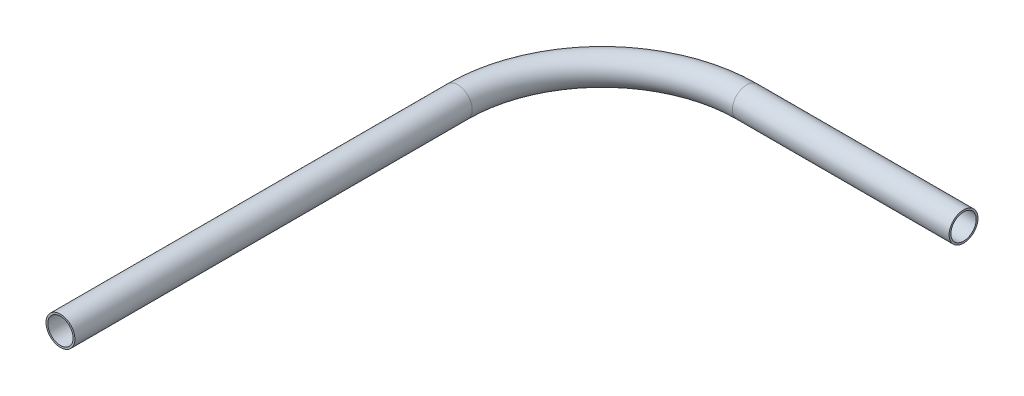
SolidWorks part; units mm, degrees
ref_plane "Спереди" through (0, 0, 0) normal (0, 0, 1) x (1, 0, 0)
ref_plane "Сверху" through (0, 0, 0) normal (0, 1, 0) x (1, 0, 0)
ref_plane "Справа" through (0, 0, 0) normal (1, 0, 0) x (0, 0, -1)
sketch "Эскиз1" plane through (0, 0, 0) normal (0, 1, 0) x (1, 0, 0)
  line L0 (-200, -300) -> (-200, -80)
  line L1 (0, 0) -> (-120, 0)
  line L2 (0, 0) -> (0, -87.0881) construction
  arc A0 (-200, -80) -> (-120, 0) centre (-120, -80) cw
  point P8 (0, 0)
  point P10 (0, 0)
  dimension "D1" = 80
  dimension "D2" = 200
  dimension "D3" = 300
sketch "Эскиз2" plane through (0, 0, 0) normal (1, 0, 0) x (0, 0, -1)
  circle A0 centre (0, 0) radius 8
  circle A1 centre (0, 0) radius 7
  dimension "D1" = 16
  dimension "D2" = 1
sweep "По траектории1" add profiles "Эскиз2" path "Эскиз1"
